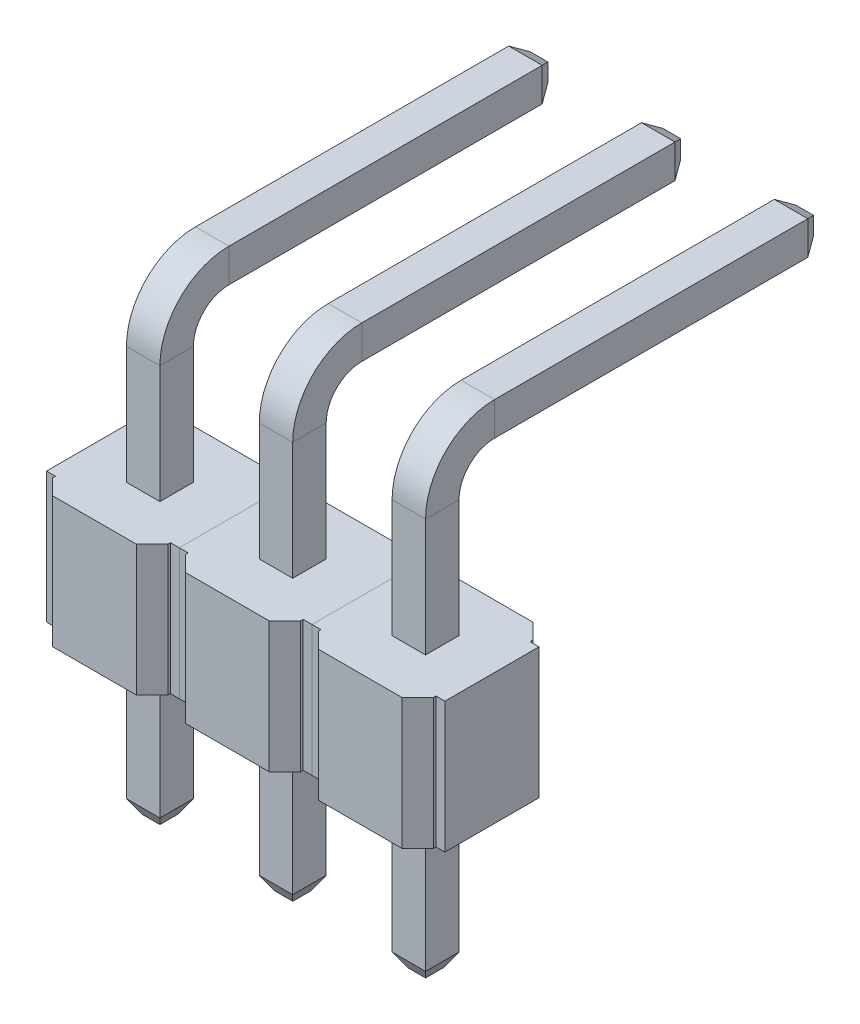
SolidWorks part; units mm, degrees
ref_plane "Front" through (0, 0, 0) normal (0, 0, 1) x (1, 0, 0)
ref_plane "Top" through (0, 0, 0) normal (0, 1, 0) x (1, 0, 0)
ref_plane "Right" through (0, 0, 0) normal (1, 0, 0) x (0, 0, -1)
sketch "Эскиз2" plane through (0, 0, 0) normal (1, 0, 0) x (0, 0, -1)
  line L0 (0, 0) -> (0, -3)
  line L1 (0, 0) -> (0, 4.75)
  line L2 (1, 5.75) -> (7.25, 5.75)
  arc A0 (1, 5.75) -> (0, 4.75) centre (1, 4.75) ccw
  point P7 (0, 5.75)
  dimension "D4" = 1
  dimension "D1" = 3
  dimension "D2" = 5.75
  dimension "D3" = 7.25
sketch "Эскиз3" plane through (0, 0, 0) normal (0, 1, 0) x (1, 0, 0)
  line L1 (-0.32, -0.32) -> (0.32, -0.32)
  line L2 (-0.32, -0.32) -> (-0.32, 0.32)
  line L3 (-0.32, 0.32) -> (0.32, 0.32)
  line L4 (0.32, -0.32) -> (0.32, 0.32)
  line L5 (-0.32, -0.32) -> (0.32, 0.32) construction
  line L6 (-0.32, 0.32) -> (0.32, -0.32) construction
  point P0 (0, 0)
sweep "По траектории1" add profiles "Эскиз3" path "Эскиз2"
chamfer "Фаска1" distance 0.15 angle 60 8 edges at (0, -3, -0.32) (-0.32, -3, 0) (0, -3, 0.32) (0.32, -3, 0) (0, 6.07, -7.25) (-0.32, 5.75, -7.25) (0, 5.43, -7.25) (0.32, 5.75, -7.25)
sketch "Эскиз4" plane through (0, 0, 0) normal (0, 1, 0) x (1, 0, 0)
  line L0 (-1.1, 0.9) -> (-1.1, 1.25)
  line L1 (-1.1, -1.25) -> (1.1, -1.25)
  line L2 (-1.1, -1.25) -> (-1.1, -0.9)
  line L3 (-1.1, 1.25) -> (1.1, 1.25)
  line L4 (1.1, -1.25) -> (1.1, -0.9)
  line L5 (-1.1, -1.25) -> (1.1, 1.25) construction
  line L6 (-1.1, 1.25) -> (1.1, -1.25) construction
  line L7 (-1.27, -0.9) -> (-1.1, -0.9)
  line L8 (-1.27, -0.9) -> (-1.27, 0.9)
  line L9 (-1.27, 0.9) -> (-1.1, 0.9)
  line L10 (1.27, -0.9) -> (1.27, 0.9)
  line L11 (-1.27, -0.9) -> (1.27, 0.9) construction
  line L12 (-1.27, 0.9) -> (1.27, -0.9) construction
  line L13 (1.1, 0.9) -> (1.1, 1.25)
  line L14 (1.1, -0.9) -> (1.27, -0.9)
  line L15 (1.1, 0.9) -> (1.27, 0.9)
  point P0 (0, 0)
  point P5 (0, 0)
  dimension "D1" = 2.2
  dimension "D2" = 2.5
  dimension "D3" = 1.8
  dimension "D4" = 2.54
extrude "Бобышка-Вытянуть1" add sketch "Эскиз4" along normal blind 2.5 separate body
chamfer "Фаска2" distance 0.3 angle 45 4 edges at (-1.1, 1.25, -1.25) (1.1, 1.25, -1.25) (-1.1, 1.25, 1.25) (1.1, 1.25, 1.25)
pattern_linear "Линейный массив1" count 3 spacing 2.54 along (-1, 0, 0) of bodies 101 102
equation "\"D2@Эскиз2\"=6.07-0.64/2"
equation "\"D3@Эскиз2\"=6+2.5/2"
